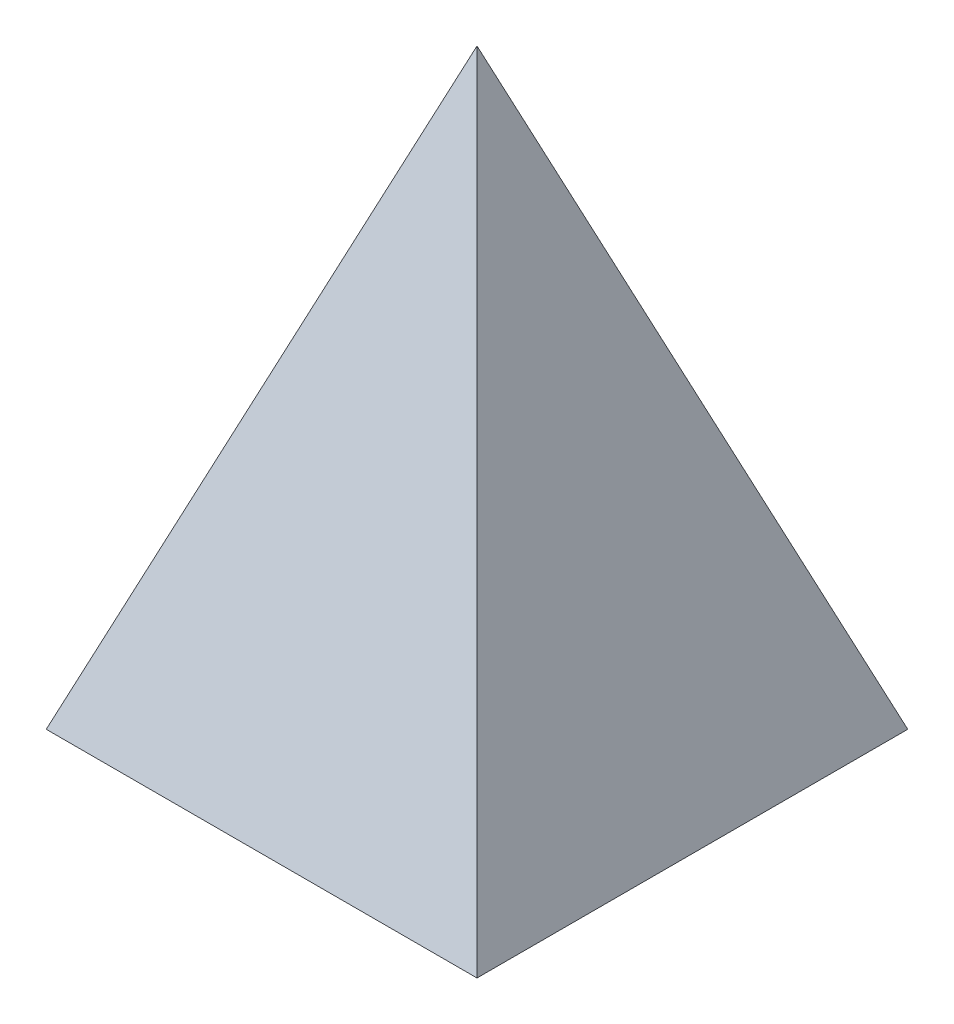
SolidWorks part; units mm, degrees
ref_plane "Front Plane" through (0, 0, 0) normal (0, 0, 1) x (1, 0, 0)
ref_plane "Top Plane" through (0, 0, 0) normal (0, 1, 0) x (1, 0, 0)
ref_plane "Right Plane" through (0, 0, 0) normal (1, 0, 0) x (0, 0, -1)
sketch "Sketch43" plane through (0, 0, 0) normal (0, 1, 0) x (1, 0, 0)
  line L1 (2.5, 2.5) -> (-2.5, 2.5)
  line L2 (2.5, 2.5) -> (2.5, -2.5)
  line L3 (2.5, -2.5) -> (-2.5, -2.5)
  line L4 (-2.5, 2.5) -> (-2.5, -2.5)
  line L5 (2.5, 2.5) -> (-2.5, -2.5) construction
  line L6 (2.5, -2.5) -> (-2.5, 2.5) construction
  point P0 (0, 0)
  dimension "D1" = 5
extrude "Boss-Extrude30" add sketch "Sketch43" along normal blind 77 draft 20
